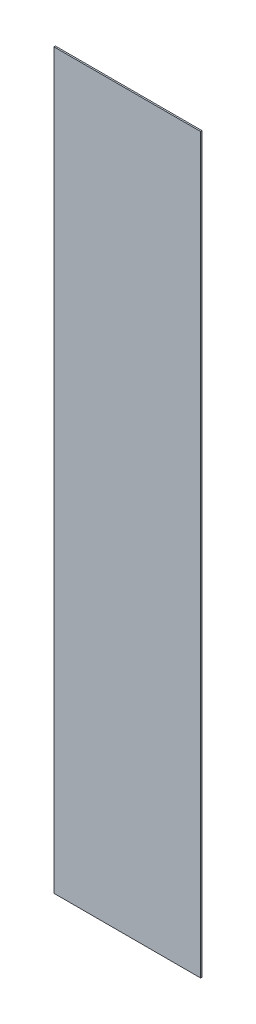
SolidWorks part; units mm, degrees
ref_plane "Front Plane" through (0, 0, 0) normal (0, 0, 1) x (1, 0, 0)
ref_plane "Top Plane" through (0, 0, 0) normal (0, 1, 0) x (1, 0, 0)
ref_plane "Right Plane" through (0, 0, 0) normal (1, 0, 0) x (0, 0, -1)
sketch "Sketch1" plane through (0, 0, 0) normal (0, 0, 1) x (1, 0, 0)
  line L1 (-5, -25) -> (5, -25)
  line L2 (-5, -25) -> (-5, 25)
  line L3 (-5, 25) -> (5, 25)
  line L4 (5, -25) -> (5, 25)
  line L5 (-5, -25) -> (5, 25) construction
  line L6 (-5, 25) -> (5, -25) construction
  point P0 (0, 0)
  dimension "D1" = 50
  dimension "D2" = 10
extrude "Boss-Extrude1" add sketch "Sketch1" along normal blind 0.1 contours L3 L4 L1 L2
